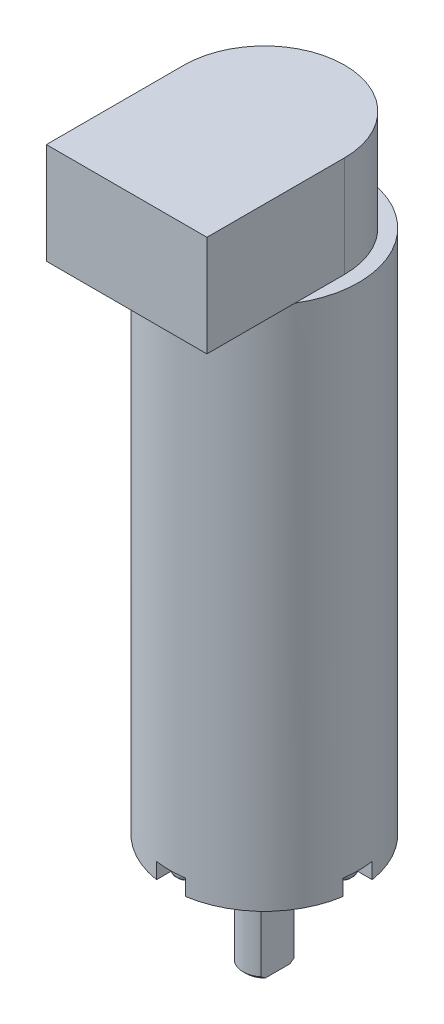
SolidWorks part; units mm, degrees
ref_plane "前视基准面" through (0, 0, 0) normal (0, 0, 1) x (1, 0, 0)
ref_plane "上视基准面" through (0, 0, 0) normal (0, 1, 0) x (1, 0, 0)
ref_plane "右视基准面" through (0, 0, 0) normal (1, 0, 0) x (0, 0, -1)
sketch "草图1" plane through (0, 0, 0) normal (0, 1, 0) x (1, 0, 0)
  circle A0 centre (0, 0) radius 17.75
  dimension "D1" = 35.5
extrude "凸台-拉伸1" add sketch "草图1" along normal blind 62.86
sketch "草图2" plane through (0, 0, 0) normal (0, -1, 0) x (1, 0, 0)
  circle A0 centre (0, 0) radius 17.75
  dimension "D1" = 35.5
extrude "凸台-拉伸3" add sketch "草图2" along normal blind 35.9 contours A0
sketch "草图4" plane through (0, -35.9, 0) normal (0, -1, 0) x (1, 0, 0)
  circle A0 centre (0, 0) radius 11
  dimension "D1" = 22
extrude "凸台-拉伸4" add sketch "草图4" along normal blind 2
sketch "草图5" plane through (0, -37.9, 0) normal (0, -1, 0) x (1, 0, 0)
  circle A0 centre (0, 0) radius 4
  dimension "D1" = 8
extrude "凸台-拉伸5" add sketch "草图5" along normal blind 19
chamfer "倒角1" distance 0.6 angle 45 1 edges at (0, -56.9, -4)
sketch "草图6" plane through (0, -35.9, 0) normal (0, -1, 0) x (1, 0, 0)
  line L0 (0, 0) -> (50000, 0) construction
  line L1 (0, 0) -> (0, 50000) construction
  line L2 (-2.75, 14.3957) -> (-2.75, 17.5357)
  line L3 (2.75, 14.3957) -> (2.75, 17.5357)
  line L4 (14.3957, 2.75) -> (17.5357, 2.75)
  line L5 (14.3957, -2.75) -> (17.5357, -2.75)
  line L6 (2.75, -14.3957) -> (2.75, -17.5357)
  line L7 (-2.75, -14.3957) -> (-2.75, -17.5357)
  line L8 (-14.3957, -2.75) -> (-17.5357, -2.75)
  line L9 (-14.3957, 2.75) -> (-17.5357, 2.75)
  arc A0 (-2.75, 14.3957) -> (2.75, 14.3957) centre (0, 14.3957) ccw
  circle A1 centre (0, 0) radius 17.75 construction
  circle A2 centre (0, 0) radius 17.75 construction
  arc A3 (-2.75, 17.5357) -> (2.75, 17.5357) centre (0, 0) cw
  arc A4 (14.3957, 2.75) -> (14.3957, -2.75) centre (14.3957, 0) ccw
  arc A5 (17.5357, 2.75) -> (17.5357, -2.75) centre (0, 0) cw
  arc A6 (2.75, -14.3957) -> (-2.75, -14.3957) centre (0, -14.3957) ccw
  arc A7 (2.75, -17.5357) -> (-2.75, -17.5357) centre (0, 0) cw
  arc A8 (-14.3957, -2.75) -> (-14.3957, 2.75) centre (-14.3957, 0) ccw
  arc A9 (-17.5357, -2.75) -> (-17.5357, 2.75) centre (0, 0) cw
  point P33 (0, 0)
  dimension "D1" = 5.5
  dimension "D2" = 3.14
  dimension "D3" = 4
extrude "切除-拉伸1" cut sketch "草图6" against normal blind 3
sketch "草图7" plane through (0, -35.9, 0) normal (0, -1, 0) x (1, 0, 0)
  line L0 (0, 0) -> (-35355.3391, 35355.3391) construction
  line L1 (0, 0) -> (50000, 0) construction
  line L2 (0, 0) -> (0, 50000) construction
  line L3 (0, 0) -> (35355.3391, 35355.3391) construction
  circle A0 centre (0, 0) radius 15 construction
  circle A1 centre (-10.6066, 10.6066) radius 1.25
  circle A2 centre (10.6066, 10.6066) radius 1.25
  circle A3 centre (-10.6066, -10.6066) radius 1.25
  circle A4 centre (10.6066, -10.6066) radius 1.25
  dimension "D3" = 30
  dimension "D4" = 2.5
  dimension "D5" = 2.5
  dimension "D6" = 2.5
  dimension "D7" = 2.5
  dimension "D1" = 45
  dimension "D2" = 45
extrude "切除-拉伸2" cut sketch "草图7" against normal blind 4 contours A1 | A2 | A4 | A3
sketch "草图8" plane through (0, -32.9, 0) normal (0, -1, 0) x (1, 0, 0)
  circle A0 centre (0, 14.3957) radius 2.25
  circle A1 centre (-14.3957, 0) radius 2.25
  circle A2 centre (14.3957, 0) radius 2.25
  circle A3 centre (0, -14.3957) radius 2.25
  dimension "D1" = 4.5
  dimension "D2" = 4.5
  dimension "D3" = 4.5
  dimension "D4" = 4.5
extrude "凸台-拉伸6" add sketch "草图8" along normal blind 2
fillet "圆角1" radius 0.6 1 edges at (0, -34.9, 12.1457)
fillet "圆角2" radius 0.6 1 edges at (-14.3957, -34.9, -2.25)
fillet "圆角3" radius 0.6 1 edges at (0, -34.9, -16.6457)
fillet "圆角4" radius 0.6 1 edges at (14.3957, -34.9, -2.25)
ref_plane "基准面1" through (0, -34.1, 0) normal (0, -1, 0) x (-1, 0, 0)
sketch "草图10" plane through (0, -34.1, 0) normal (0, -1, 0) x (-1, 0, 0)
  line L0 (0, -14.3957) -> (5.1626, -14.3957) construction
  line L1 (5.1626, -14.3957) -> (0, -14.3957) construction
  line L2 (0, -14.3957) -> (0, -9.7796) construction
  line L3 (0.3, -12.217) -> (0.3, -13.717)
  line L4 (0.6787, -14.0957) -> (2.1787, -14.0957)
  line L5 (-0.6787, -14.0957) -> (-2.1787, -14.0957)
  line L6 (-0.3, -12.217) -> (-0.3, -13.717)
  line L7 (-0.3, -16.5743) -> (-0.3, -15.0743)
  line L8 (-0.6787, -14.6957) -> (-2.1787, -14.6957)
  line L9 (0.3, -16.5743) -> (0.3, -15.0743)
  line L10 (0.6787, -14.6957) -> (2.1787, -14.6957)
  line L11 (-12.217, 0.3) -> (-13.717, 0.3)
  line L12 (-12.217, -0.3) -> (-13.717, -0.3)
  line L13 (-14.0957, 0.6787) -> (-14.0957, 2.1787)
  line L14 (-14.6957, 0.6787) -> (-14.6957, 2.1787)
  line L15 (-16.5743, 0.3) -> (-15.0743, 0.3)
  line L16 (-16.5743, -0.3) -> (-15.0743, -0.3)
  line L17 (-14.6957, -0.6787) -> (-14.6957, -2.1787)
  line L18 (-14.0957, -0.6787) -> (-14.0957, -2.1787)
  line L19 (0.3, 12.217) -> (0.3, 13.717)
  line L20 (-0.3, 12.217) -> (-0.3, 13.717)
  line L21 (0.6787, 14.0957) -> (2.1787, 14.0957)
  line L22 (0.6787, 14.6957) -> (2.1787, 14.6957)
  line L23 (0.3, 16.5743) -> (0.3, 15.0743)
  line L24 (-0.3, 16.5743) -> (-0.3, 15.0743)
  line L25 (-0.6787, 14.6957) -> (-2.1787, 14.6957)
  line L26 (-0.6787, 14.0957) -> (-2.1787, 14.0957)
  line L27 (12.217, -0.3) -> (13.717, -0.3)
  line L28 (12.217, 0.3) -> (13.717, 0.3)
  line L29 (14.0957, -0.6787) -> (14.0957, -2.1787)
  line L30 (14.6957, -0.6787) -> (14.6957, -2.1787)
  line L31 (16.5743, -0.3) -> (15.0743, -0.3)
  line L32 (16.5743, 0.3) -> (15.0743, 0.3)
  line L33 (14.6957, 0.6787) -> (14.6957, 2.1787)
  line L34 (14.0957, 0.6787) -> (14.0957, 2.1787)
  circle A0 centre (0, -14.3957) radius 2.1992 construction
  arc A1 (0.3, -13.717) -> (0.6787, -14.0957) centre (0.6787, -13.717) ccw
  arc A2 (-0.3, -13.717) -> (-0.6787, -14.0957) centre (-0.6787, -13.717) cw
  arc A3 (-0.3, -15.0743) -> (-0.6787, -14.6957) centre (-0.6787, -15.0743) ccw
  arc A4 (0.3, -15.0743) -> (0.6787, -14.6957) centre (0.6787, -15.0743) cw
  arc A5 (-2.1787, -14.0957) -> (-2.1787, -14.6957) centre (0, -14.3957) ccw
  arc A6 (-0.3, -12.217) -> (0.3, -12.217) centre (0, -14.3957) cw
  arc A7 (2.1787, -14.0957) -> (2.1787, -14.6957) centre (0, -14.3957) cw
  arc A8 (-0.3, -16.5743) -> (0.3, -16.5743) centre (0, -14.3957) ccw
  arc A9 (-12.217, 0.3) -> (-12.217, -0.3) centre (-14.3957, 0) cw
  arc A10 (-13.717, 0.3) -> (-14.0957, 0.6787) centre (-13.717, 0.6787) cw
  arc A11 (-13.717, -0.3) -> (-14.0957, -0.6787) centre (-13.717, -0.6787) ccw
  arc A12 (-14.0957, 2.1787) -> (-14.6957, 2.1787) centre (-14.3957, 0) ccw
  arc A13 (-15.0743, 0.3) -> (-14.6957, 0.6787) centre (-15.0743, 0.6787) ccw
  arc A14 (-16.5743, 0.3) -> (-16.5743, -0.3) centre (-14.3957, 0) ccw
  arc A15 (-15.0743, -0.3) -> (-14.6957, -0.6787) centre (-15.0743, -0.6787) cw
  arc A16 (-14.0957, -2.1787) -> (-14.6957, -2.1787) centre (-14.3957, 0) cw
  arc A17 (0.3, 12.217) -> (-0.3, 12.217) centre (0, 14.3957) cw
  arc A18 (0.3, 13.717) -> (0.6787, 14.0957) centre (0.6787, 13.717) cw
  arc A19 (-0.3, 13.717) -> (-0.6787, 14.0957) centre (-0.6787, 13.717) ccw
  arc A20 (2.1787, 14.0957) -> (2.1787, 14.6957) centre (0, 14.3957) ccw
  arc A21 (0.3, 15.0743) -> (0.6787, 14.6957) centre (0.6787, 15.0743) ccw
  arc A22 (0.3, 16.5743) -> (-0.3, 16.5743) centre (0, 14.3957) ccw
  arc A23 (-0.3, 15.0743) -> (-0.6787, 14.6957) centre (-0.6787, 15.0743) cw
  arc A24 (-2.1787, 14.0957) -> (-2.1787, 14.6957) centre (0, 14.3957) cw
  arc A25 (12.217, -0.3) -> (12.217, 0.3) centre (14.3957, 0) cw
  arc A26 (13.717, -0.3) -> (14.0957, -0.6787) centre (13.717, -0.6787) cw
  arc A27 (13.717, 0.3) -> (14.0957, 0.6787) centre (13.717, 0.6787) ccw
  arc A28 (14.0957, -2.1787) -> (14.6957, -2.1787) centre (14.3957, 0) ccw
  arc A29 (15.0743, -0.3) -> (14.6957, -0.6787) centre (15.0743, -0.6787) ccw
  arc A30 (16.5743, -0.3) -> (16.5743, 0.3) centre (14.3957, 0) ccw
  arc A31 (15.0743, 0.3) -> (14.6957, 0.6787) centre (15.0743, 0.6787) cw
  arc A32 (14.0957, 2.1787) -> (14.6957, 2.1787) centre (14.3957, 0) cw
  point P105 (0, 0)
  dimension "D4" = 4
  dimension "D1" = 1.5
  dimension "D2" = 1.5
  dimension "D3" = 0.3
extrude "切除-拉伸3" cut sketch "草图10" along normal blind 2
sketch "草图11" plane through (0, -56.9, 0) normal (0, -1, 0) x (1, 0, 0)
  line L0 (0.2147, 0) -> (50000.2147, 0) construction
  line L1 (0, 0) -> (0, 50000) construction
  line L2 (2.5, 2.9286) -> (2.5, -2.9286)
  line L3 (2.5, 2.9286) -> (2.5, 3.1225)
  line L4 (2.5, -2.9286) -> (2.5, -3.1225)
  circle A0 centre (0, 0) radius 3.8506 construction
  circle A2 centre (0, 0) radius 4 construction
  arc A3 (2.5, 3.1225) -> (2.5, -3.1225) centre (0, 0) cw
  dimension "D1" = 2.5
extrude "切除-拉伸4" cut sketch "草图11" against normal blind 17
sketch "草图12" plane through (0, 62.86, 0) normal (0, 1, 0) x (1, 0, 0)
  line L0 (0.2405, 0) -> (50000.2405, 0) construction
  line L1 (0, 0) -> (0, 50000) construction
  line L2 (-15.1, 0) -> (-15.1, -25.9)
  line L3 (-15.1, -25.9) -> (15.1, -25.9)
  line L4 (15.1, 0) -> (15.1, -25.9)
  arc A0 (15.1, 0) -> (-15.1, 0) centre (0, 0) ccw
  point P11 (0, -25.9)
  dimension "D1" = 30.2
  dimension "D2" = 25.9
extrude "凸台-拉伸7" add sketch "草图12" along normal blind 19
